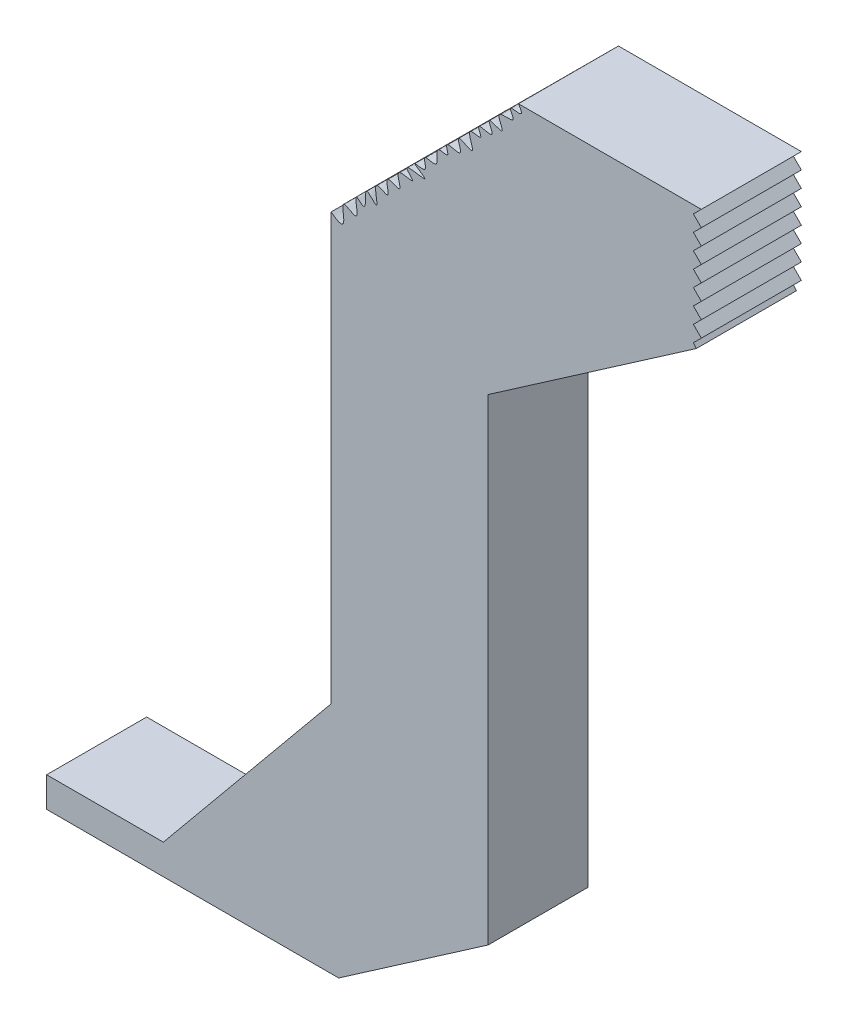
SolidWorks part; units mm, degrees
material "Plain Carbon Steel"
ref_plane "Front Plane" through (0, 0, 0) normal (0, 0, 1) x (1, 0, 0)
ref_plane "Top Plane" through (0, 0, 0) normal (0, 1, 0) x (1, 0, 0)
ref_plane "Right Plane" through (0, 0, 0) normal (1, 0, 0) x (0, 0, -1)
sketch "Sketch1" plane through (0, 0, 0) normal (0, 0, 1) x (1, 0, 0)
  line L14 (27.5973, 24.9802) -> (27.4379, 24.8208)
  line L15 (27.4379, 24.8208) -> (27.5973, 24.6615)
  line L16 (27.5973, 24.6615) -> (27.4379, 24.5021)
  line L17 (27.4379, 24.5021) -> (27.5973, 24.3428)
  line L18 (27.5973, 24.3428) -> (27.4379, 24.1835)
  line L19 (27.4379, 24.1835) -> (27.5973, 24.0241)
  line L20 (27.5973, 24.0241) -> (27.4379, 23.8648)
  line L21 (27.4379, 23.8648) -> (27.5973, 23.7054)
  line L25 (27.5973, 23.7054) -> (27.4379, 23.5461)
  line L26 (27.4379, 23.5461) -> (27.5973, 23.3867)
  line L28 (14.5048, 8.6415) -> (16.8389, 8.6415)
  line L29 (14.5048, 8.0415) -> (17.498, 8.0415)
  line L30 (14.5048, 8.6415) -> (14.5048, 8.0415)
  line L34 (20.1938, 12.7148) -> (20.1938, 14.6489)
  line L35 (20.1938, 14.6489) -> (20.1938, 21.234)
  line L37 (23.9399, 24.9802) -> (27.5973, 24.9802)
  line L39 (27.497, 22.5186) -> (24.7045, 20.5884)
  line L40 (24.7045, 20.5884) -> (23.3341, 19.6411)
  line L41 (23.3341, 19.6411) -> (23.3341, 10.1078)
  line L42 (23.3341, 10.1078) -> (20.3448, 8.0415)
  line L43 (20.3448, 8.0415) -> (17.998, 8.0415)
  line L44 (16.8389, 8.6415) -> (20.1938, 12.7148)
  line L45 (27.5973, 23.3867) -> (27.4379, 23.2274)
  line L46 (27.4379, 23.2274) -> (27.5973, 23.068)
  line L47 (27.5973, 23.068) -> (27.4379, 22.9087)
  line L48 (27.4379, 22.9087) -> (27.5973, 22.7494)
  line L49 (27.5973, 22.7494) -> (27.4379, 22.59)
  line L50 (27.4379, 22.59) -> (27.497, 22.5186)
  line L51 (17.498, 8.0415) -> (17.998, 8.0415)
  spline S0 degree 3 poles (20.1938, 21.234) (20.6303, 20.8962) (20.207, 21.7551) (20.8384, 21.2288) (20.5897, 21.909) (20.9429, 21.5004) (20.806, 22.1491) (21.2272, 21.5822) (20.9616, 22.326) (21.4414, 21.9485) (21.1931, 22.514) (21.697, 22.1744) (21.3868, 22.7315) (21.978, 22.4872) (21.5046, 22.8824) (22.345, 22.6224) (21.6933, 22.9827) (22.1727, 22.8217) (21.969, 23.2088) (22.415, 22.9865) (22.2194, 23.4858) (22.5976, 23.3105) (22.4078, 23.669) (22.9126, 23.4049) (22.6087, 23.9423) (23.1893, 23.5171) (22.814, 24.144) (23.2798, 23.938) (23.0254, 24.303) (23.5582, 24.0504) (23.2164, 24.5327) (23.769, 24.1998) (23.3848, 24.7244) (23.9628, 24.5506) (23.632, 24.9611) (24.1291, 24.7132) (23.9399, 24.9802) knots 0 0 0 0 0.060948 0.090021 0.127688 0.146959 0.180988 0.208228 0.248065 0.273087 0.304302 0.331767 0.363053 0.394214 0.416566 0.457513 0.486639 0.509347 0.532055 0.556987 0.589769 0.609885 0.628221 0.658724 0.686123 0.71791 0.754509 0.777527 0.796382 0.826923 0.852067 0.881774 0.911458 0.944242 0.963522 1 1 1 1
  dimension "D8" = 2.9932
extrude "Boss-Extrude1" add sketch "Sketch1" along normal blind 2 contours L35 S0 L37 L14 L15 L16 L17 L18 L19 L20 L21 L25 L26 L45 L46 L47 L48 L49 L50 L39 L40 L41 L42 L43 L51 L29 L30 L28 L44 L34
sketch "Sketch2" plane through (0, 8.0415, 0) normal (0, -1, 0) x (1, 0, 0)
  line L0 (14.5048, 1) -> (18.9187, 1)
  line L1 (14.5048, 2) -> (14.5048, 0) construction
